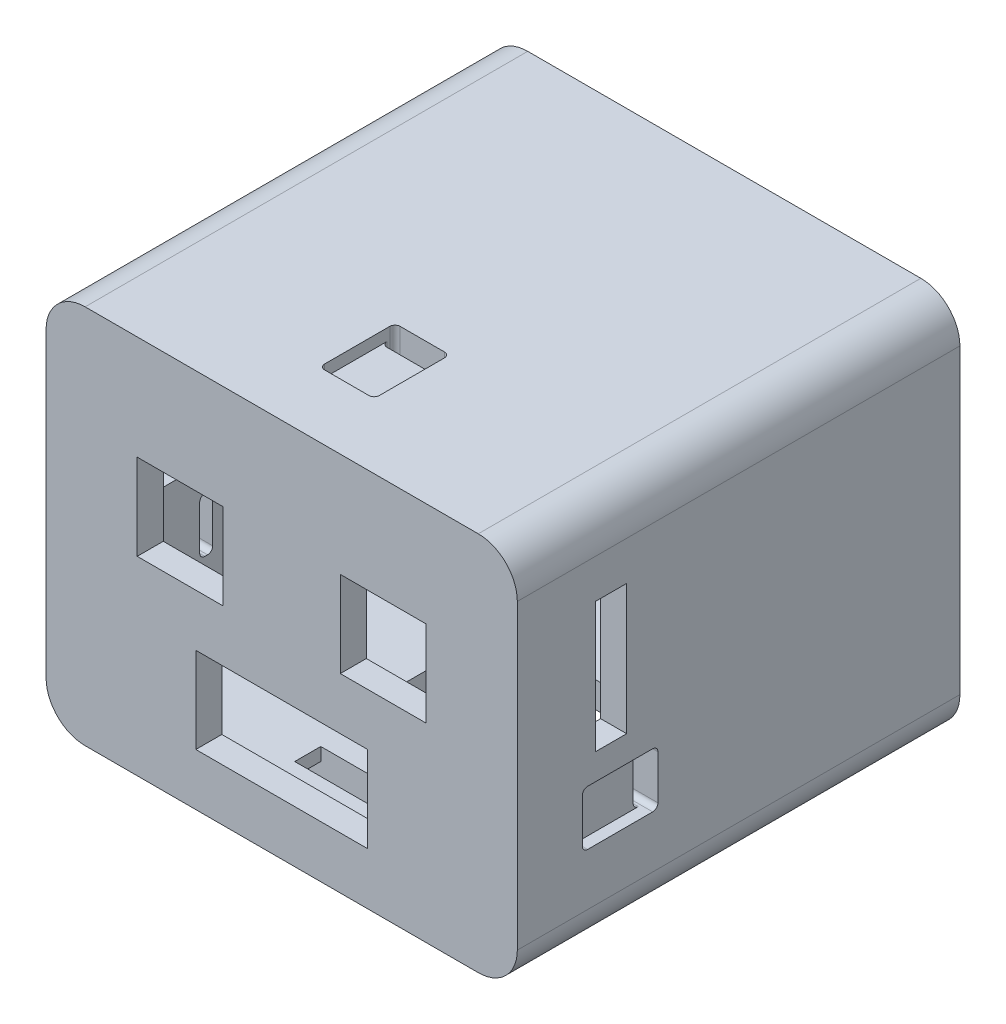
SolidWorks part; units mm, degrees
ref_plane "Front Plane" through (0, 0, 0) normal (0, 0, 1) x (1, 0, 0)
ref_plane "Top Plane" through (0, 0, 0) normal (0, 1, 0) x (1, 0, 0)
ref_plane "Right Plane" through (0, 0, 0) normal (1, 0, 0) x (0, 0, -1)
sketch "Sketch1" plane through (0, 0, 0) normal (0, 0, 1) x (1, 0, 0)
  line L1 (15, 0) -> (166, 0)
  line L2 (0, 15) -> (0, 131)
  line L3 (15, 146) -> (166, 146)
  line L4 (181, 15) -> (181, 131)
  line L5 (57.5, 20) -> (123.5, 20)
  line L6 (57.5, 20) -> (57.5, 53)
  line L7 (57.5, 53) -> (123.5, 53)
  line L8 (123.5, 20) -> (123.5, 53)
  line L9 (35, 106) -> (68, 106)
  line L10 (35, 106) -> (35, 73)
  line L11 (35, 73) -> (68, 73)
  line L12 (68, 106) -> (68, 73)
  line L13 (35, 106) -> (68, 73) construction
  line L14 (35, 73) -> (68, 106) construction
  line L19 (113, 106) -> (146, 106)
  line L20 (113, 106) -> (113, 73)
  line L21 (113, 73) -> (146, 73)
  line L22 (146, 106) -> (146, 73)
  line L23 (113, 106) -> (146, 73) construction
  line L24 (113, 73) -> (146, 106) construction
  arc A0 (166, 0) -> (181, 15) centre (166, 15) ccw
  arc A1 (0, 15) -> (15, 0) centre (15, 15) ccw
  arc A2 (15, 146) -> (0, 131) centre (15, 131) ccw
  arc A3 (166, 146) -> (181, 131) centre (166, 131) cw
  point P13 (181, 0)
  point P16 (0, 0)
  point P19 (0, 146)
  point P29 (51.5, 89.5)
  point P30 (129.5, 89.5)
  point P32 (90.5, 53)
  point P33 (90.5, 146)
  dimension "D7" = 15
  dimension "D1" = 66
  dimension "D2" = 33
  dimension "D3" = 45
  dimension "D4" = 20
  dimension "D5" = 33
  dimension "D6" = 33
  dimension "D8" = 33
  dimension "D9" = 33
  dimension "D10" = 35
  dimension "D11" = 35
  dimension "D12" = 40
  dimension "D13" = 20
extrude "Boss-Extrude1" add sketch "Sketch1" against normal blind 170
sketch "Sketch3" plane through (0, 0, -170) normal (0, 0, -1) x (-1, 0, 0)
  line L8 (-166, 146) -> (-15, 146) construction
  line L9 (-171, 136) -> (-10, 136)
  line L10 (-171, 136) -> (-171, 10)
  line L11 (-171, 10) -> (-10, 10)
  line L12 (-10, 136) -> (-10, 10)
  line L13 (-171, 136) -> (-10, 10) construction
  line L14 (-171, 10) -> (-10, 136) construction
  line L15 (0, 131) -> (0, 15) construction
  line L16 (-181, 15) -> (-181, 131) construction
  line L17 (-15, 0) -> (-166, 0) construction
  point P6 (-90.5, 73)
  dimension "D1" = 10
  dimension "D2" = 10
  dimension "D3" = 10
  dimension "D4" = 10
extrude "Cut-Extrude1" cut sketch "Sketch3" against normal offset from surface (160 mm away) 10 up to face at (51.5, 89.5, 0)
sketch "Sketch4" plane through (0, 146, 0) normal (0, 1, 0) x (1, 0, 0)
  line L0 (166, 170) -> (166, 0) construction
  line L1 (82, 54) -> (99, 54)
  line L2 (80, 52) -> (80, 27)
  line L3 (82, 25) -> (99, 25)
  line L4 (101, 52) -> (101, 27)
  line L5 (80, 54) -> (101, 25) construction
  line L6 (80, 25) -> (101, 54) construction
  line L8 (166, 0) -> (15, 0) construction
  arc A0 (101, 52) -> (99, 54) centre (99, 52) ccw
  arc A1 (101, 27) -> (99, 25) centre (99, 27) cw
  arc A2 (80, 27) -> (82, 25) centre (82, 27) ccw
  arc A3 (80, 52) -> (82, 54) centre (82, 52) cw
  point P4 (90.5, 39.5)
  dimension "D5" = 2
  dimension "D1" = 29
  dimension "D2" = 21
  dimension "D3" = 65
  dimension "D4" = 25
extrude "Cut-Extrude2" cut sketch "Sketch4" against normal blind 4.5
sketch "Sketch5" plane through (0, 141.5, 0) normal (0, 1, 0) x (1, 0, 0)
  line L0 (80, 52) -> (80, 27) construction
  line L1 (82, 49) -> (99, 49)
  line L2 (80, 51) -> (80, 52)
  line L3 (82, 54) -> (99, 54)
  line L4 (101, 51) -> (101, 52)
  line L5 (80, 49) -> (101, 54) construction
  line L6 (80, 54) -> (101, 49) construction
  line L8 (101, 27) -> (101, 52) construction
  line L9 (99, 54) -> (82, 54) construction
  arc A0 (99, 54) -> (101, 52) centre (99, 52) cw
  arc A1 (101, 51) -> (99, 49) centre (99, 51) cw
  arc A2 (80, 51) -> (82, 49) centre (82, 51) ccw
  arc A3 (80, 52) -> (82, 54) centre (82, 52) cw
  point P4 (90.5, 51.5)
  dimension "D2" = 2
  dimension "D1" = 5
extrude "Cut-Extrude3" cut sketch "Sketch5" against normal blind 18.5
ref_plane "Plane1" through (0, 0, -30) normal (0, 0, 1) x (1, 0, 0)
sketch "Sketch6" plane through (0, 0, -30) normal (0, 0, 1) x (1, 0, 0)
  line L1 (226.7676, 116) -> (-8.745, 116)
  line L2 (226.7676, 116) -> (226.7676, 66)
  line L3 (226.7676, 66) -> (-8.745, 66)
  line L4 (-8.745, 116) -> (-8.745, 66)
  line L5 (226.7676, 116) -> (-8.745, 66) construction
  line L6 (226.7676, 66) -> (-8.745, 116) construction
  line L11 (166, 146) -> (15, 146) construction
  point P4 (109.0113, 91)
  dimension "50" = 50
  dimension "D9" = 30
extrude "Cut-Extrude4" cut sketch "Sketch6" against normal blind 12 contours L2 L3 L4 L1
sketch "Sketch7" plane through (181, 0, 0) normal (1, 0, 0) x (0, 0, -1)
  line L0 (0, 15) -> (0, 131) construction
  line L1 (27, 56) -> (52, 56)
  line L2 (25, 54) -> (25, 37)
  line L3 (27, 35) -> (52, 35)
  line L4 (54, 54) -> (54, 37)
  line L5 (25, 56) -> (54, 35) construction
  line L6 (25, 35) -> (54, 56) construction
  line L7 (42, 66) -> (30, 66) construction
  arc A0 (25, 54) -> (27, 56) centre (27, 54) cw
  arc A1 (25, 37) -> (27, 35) centre (27, 37) ccw
  arc A2 (52, 35) -> (54, 37) centre (52, 37) ccw
  arc A3 (54, 54) -> (52, 56) centre (52, 54) ccw
  point P4 (39.5, 45.5)
  dimension "D5" = 2
  dimension "D1" = 29
  dimension "D2" = 21
  dimension "D3" = 25
  dimension "D4" = 10
extrude "Cut-Extrude5" cut sketch "Sketch7" against normal blind 4.5
sketch "Sketch8" plane through (176.5, 0, 0) normal (1, 0, 0) x (0, 0, -1)
  line L0 (52, 56) -> (27, 56) construction
  line L1 (51, 56) -> (52, 56)
  line L2 (49, 54) -> (49, 37)
  line L3 (51, 35) -> (52, 35)
  line L4 (54, 54) -> (54, 37)
  line L5 (49, 56) -> (54, 35) construction
  line L6 (49, 35) -> (54, 56) construction
  line L7 (54, 37) -> (54, 54) construction
  line L8 (27, 35) -> (52, 35) construction
  arc A0 (51, 35) -> (49, 37) centre (51, 37) cw
  arc A1 (52, 35) -> (54, 37) centre (52, 37) ccw
  arc A2 (54, 54) -> (52, 56) centre (52, 54) ccw
  arc A3 (51, 56) -> (49, 54) centre (51, 54) ccw
  point P4 (51.5, 45.5)
  dimension "D2" = 2
  dimension "D1" = 5
extrude "Cut-Extrude6" cut sketch "Sketch8" against normal blind 10
ref_plane "Plane2" through (90.5, 0, 0) normal (1, 0, 0) x (0, 0, -1)
mirror "Mirror1" about plane through (90.5, 0, 0) normal (1, 0, 0) of "Cut-Extrude6", "Cut-Extrude5"
sketch "Sketch9" plane through (0, 0, 0) normal (0, -1, 0) x (1, 0, 0)
  line L0 (15, 0) -> (166, 0) construction
  line L1 (60.5, -25) -> (120.5, -25)
  line L2 (60.5, -25) -> (60.5, -35)
  line L3 (60.5, -35) -> (120.5, -35)
  line L4 (120.5, -25) -> (120.5, -35)
  line L5 (60.5, -25) -> (120.5, -35) construction
  line L6 (60.5, -35) -> (120.5, -25) construction
  line L7 (60.5, -140) -> (120.5, -140)
  line L8 (60.5, -140) -> (60.5, -150)
  line L9 (60.5, -150) -> (120.5, -150)
  line L10 (120.5, -140) -> (120.5, -150)
  line L11 (60.5, -140) -> (120.5, -150) construction
  line L12 (60.5, -150) -> (120.5, -140) construction
  line L13 (15, -170) -> (166, -170) construction
  line L14 (166, -170) -> (166, 0) construction
  point P4 (90.5, -30)
  point P9 (90.5, -145)
  dimension "D1" = 10
  dimension "D2" = 10
  dimension "D3" = 25
  dimension "D4" = 20
  dimension "D5" = 60
  dimension "D6" = 60
  dimension "D7" = 45.5
  dimension "D8" = 45.5
extrude "Cut-Extrude7" cut sketch "Sketch9" against normal blind 5
sketch "Sketch10" plane through (0, 5, 0) normal (0, -1, 0) x (1, 0, 0)
  line L0 (120.5, -25) -> (60.5, -25) construction
  line L1 (70.5, -25) -> (110.5, -25)
  line L2 (70.5, -25) -> (70.5, -35)
  line L3 (70.5, -35) -> (110.5, -35)
  line L4 (110.5, -25) -> (110.5, -35)
  line L5 (70.5, -25) -> (110.5, -35) construction
  line L6 (70.5, -35) -> (110.5, -25) construction
  line L7 (60.5, -35) -> (120.5, -35) construction
  line L8 (120.5, -140) -> (60.5, -140) construction
  line L9 (70.5, -140) -> (110.5, -140)
  line L10 (70.5, -140) -> (70.5, -150)
  line L11 (70.5, -150) -> (110.5, -150)
  line L12 (110.5, -140) -> (110.5, -150)
  line L13 (70.5, -140) -> (110.5, -150) construction
  line L14 (70.5, -150) -> (110.5, -140) construction
  line L15 (60.5, -150) -> (120.5, -150) construction
  line L16 (60.5, -25) -> (60.5, -35) construction
  line L17 (120.5, -35) -> (120.5, -25) construction
  line L18 (120.5, -150) -> (120.5, -140) construction
  line L19 (60.5, -140) -> (60.5, -150) construction
  point P4 (90.5, -30)
  point P13 (90.5, -145)
  dimension "D1" = 10
  dimension "D2" = 10
  dimension "D3" = 10
  dimension "D4" = 10
extrude "Cut-Extrude8" cut sketch "Sketch10" against normal blind 5
sketch "Sketch11" plane through (0, 10, 0) normal (0, 1, 0) x (1, 0, 0)
  line L0 (166, 170) -> (15, 170) construction
  line L1 (65.5, 110) -> (115.5, 110)
  line L2 (65.5, 110) -> (65.5, 60)
  line L3 (65.5, 60) -> (115.5, 60)
  line L4 (115.5, 110) -> (115.5, 60)
  line L5 (65.5, 110) -> (115.5, 60) construction
  line L6 (65.5, 60) -> (115.5, 110) construction
  line L7 (15, 0) -> (166, 0) construction
  point P4 (90.5, 85)
  point P5 (90.5, 110)
  point P6 (90.5, 170)
  point P7 (90.5, 87.6458)
  dimension "D1" = 50
  dimension "D2" = 50
  dimension "D3" = 60
extrude "Cut-Extrude11" cut sketch "Sketch11" against normal blind 3
sketch "Sketch12" plane through (0, 7, 0) normal (0, 1, 0) x (1, 0, 0)
  line L0 (75.5, 110) -> (105.5, 110)
  line L1 (105.5, 110) -> (115.5, 100)
  line L2 (115.5, 100) -> (115.5, 70)
  line L3 (115.5, 70) -> (105.5, 60)
  line L4 (105.5, 60) -> (75.5, 60)
  line L5 (75.5, 60) -> (65.5, 70)
  line L6 (65.5, 70) -> (65.5, 100)
  line L7 (65.5, 100) -> (75.5, 110)
  line L8 (166, 170) -> (15, 170) construction
  line L9 (166, 0) -> (15, 0) construction
  point P2 (90.5, 110)
  point P11 (90.5, 170)
  dimension "D1" = 50
  dimension "D2" = 50
  dimension "D3" = 30
  dimension "D4" = 30
  dimension "D5" = 30
  dimension "D6" = 30
  dimension "D7" = 60
extrude "Cut-Extrude12" cut sketch "Sketch12" against normal blind 10
